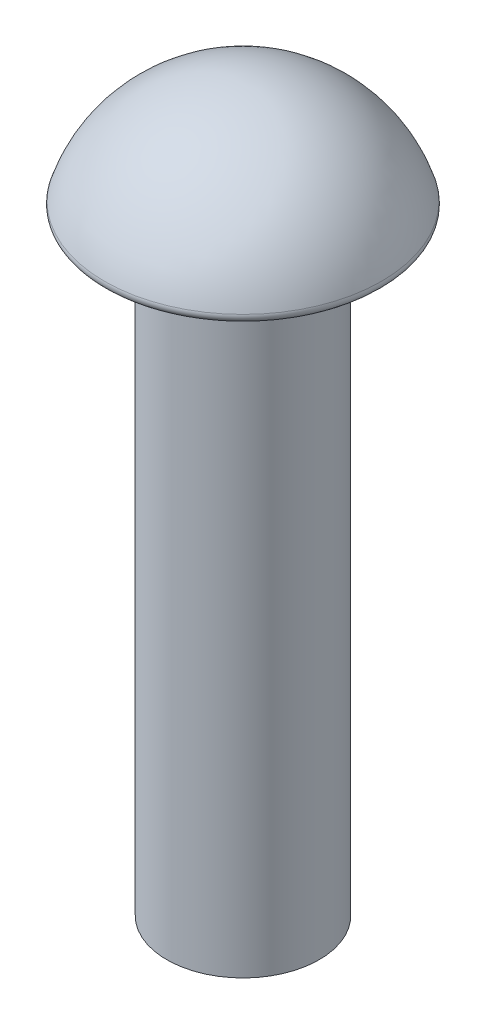
SolidWorks part; units mm, degrees
material "Alloy Steel"
ref_plane "Front Plane" through (0, 0, 0) normal (0, 0, 1) x (1, 0, 0)
ref_plane "Top Plane" through (0, 0, 0) normal (0, 1, 0) x (1, 0, 0)
ref_plane "Right Plane" through (0, 0, 0) normal (1, 0, 0) x (0, 0, -1)
sketch "Sketch2" plane through (0, 0, 0) normal (1, 0, 0) x (0, 0, -1)
  line L0 (0, 0) -> (0, 13)
  line L1 (0, 0) -> (1.375, 0)
  line L2 (1.375, 0) -> (1.375, 11)
  line L3 (1.375, 11) -> (2.3807, 11)
  line L4 (0, 13) -> (2.5, 13) construction
  line L5 (2.5, 13) -> (2.5, 11) construction
  arc A0 (0, 13) -> (2.5, 11.1623) centre (0, 10.3807) cw
  arc A1 (2.5, 11.1623) -> (2.3807, 11) centre (2.3807, 11.125) cw
  dimension "D3" = 0.125
  dimension "D1" = 1.375
  dimension "D2" = 13
  dimension "D4" = 2.5
  dimension "D5" = 2
revolve "Revolve1" add sketch "Sketch2" angle 360 about L0
